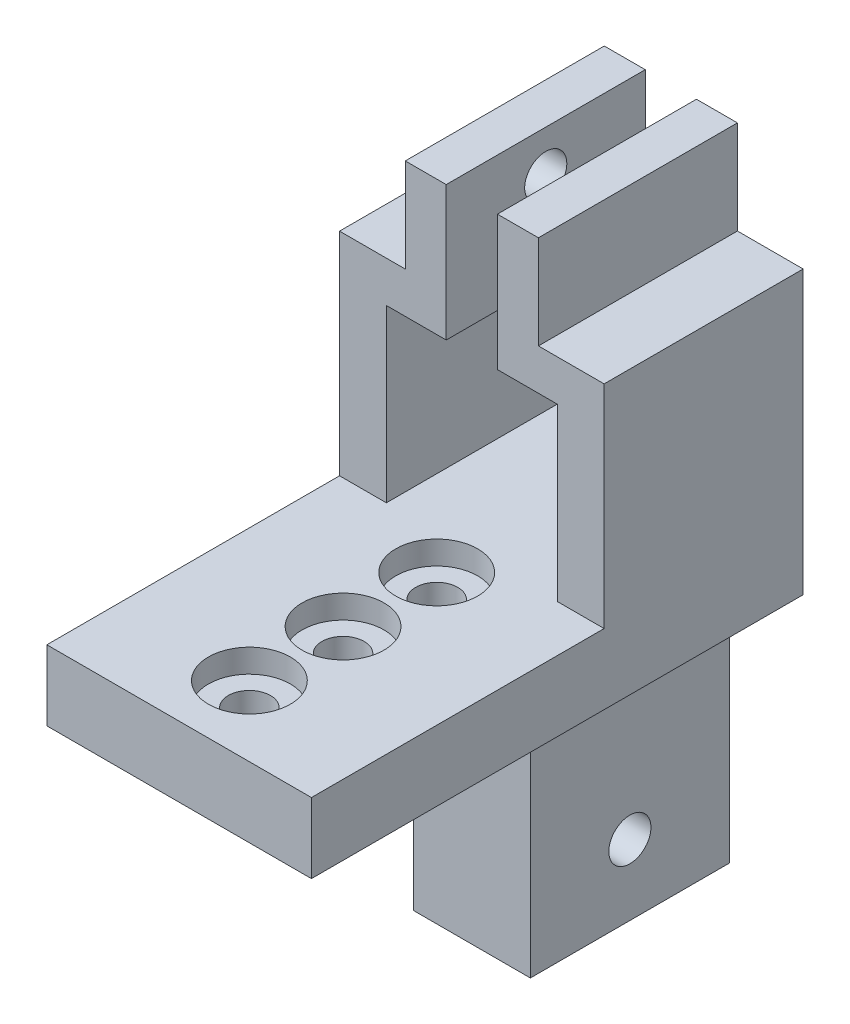
SolidWorks part; units mm, degrees
ref_plane "Front Plane" through (0, 0, 0) normal (0, 0, 1) x (1, 0, 0)
ref_plane "Top Plane" through (0, 0, 0) normal (0, 1, 0) x (1, 0, 0)
ref_plane "Right Plane" through (0, 0, 0) normal (1, 0, 0) x (0, 0, -1)
sketch "Sketch2" plane through (0, 0, 0) normal (0, 0, 1) x (1, 0, 0)
  line L0 (-7.5263, 9.46) -> (-7.5263, -5.14)
  line L1 (-7.5263, -5.14) -> (7.0737, -5.14)
  line L2 (7.0737, -5.14) -> (7.0737, 9.46)
  line L3 (7.0737, 9.46) -> (1.9603, 9.46)
  line L4 (-7.5263, 9.46) -> (-2.4129, 9.46)
  line L5 (-5.9129, 12.96) -> (-5.9129, 20.96)
  line L6 (-5.9129, 12.96) -> (-11.5263, 12.96)
  line L7 (-11.5263, 12.96) -> (-11.5263, -11.14)
  line L8 (-11.5263, -11.14) -> (11.0737, -11.14)
  line L9 (11.0737, -11.14) -> (11.0737, 12.96)
  line L10 (11.0737, 12.96) -> (5.4603, 12.96)
  line L11 (-5.9129, 20.96) -> (-2.4129, 20.96)
  line L12 (-2.4129, 20.96) -> (-2.4129, 9.46)
  line L13 (1.9603, 9.46) -> (1.9603, 20.96)
  line L14 (1.9603, 20.96) -> (5.4603, 20.96)
  line L15 (5.4603, 20.96) -> (5.4603, 12.96)
  dimension "D1" = 14.6
  dimension "D2" = 4
  dimension "D3" = 6
  dimension "D4" = 4
  dimension "D5" = 3.5
  dimension "D6" = 3.5
  dimension "D7" = 14.6
  dimension "D8" = 8
extrude "Boss-Extrude1" add sketch "Sketch2" along normal blind 17
sketch "Sketch3" plane through (0, 0, 17) normal (0, 0, 1) x (1, 0, 0)
  line L0 (-11.5263, -11.14) -> (11.0737, -11.14) construction
  line L1 (-5.2263, -11.14) -> (4.7737, -11.14)
  line L2 (-5.2263, -11.14) -> (-5.2263, -34.14)
  line L3 (-5.2263, -34.14) -> (4.7737, -34.14)
  line L4 (4.7737, -11.14) -> (4.7737, -34.14)
  line L5 (-0.2263, -11.14) -> (-0.2263, 19.7191) construction
  dimension "D1" = 10
  dimension "D2" = 23
extrude "Boss-Extrude2" add sketch "Sketch3" against normal up to surface (17 mm away) up to face at (-0.2263, 8.81, 0)
sketch "Sketch4" plane through (4.7737, 0, 0) normal (1, 0, 0) x (0, 0, -1)
  line L0 (-8.5, -34.14) -> (-8.5, 20.96) construction
  line L1 (0, -34.14) -> (-17, -34.14) construction
  line L2 (-17, 20.96) -> (0, 20.96) construction
  circle A0 centre (-8.5, -28.14) radius 1.8
  circle A1 centre (-8.5, 17.36) radius 1.8
  dimension "D1" = 3.6
  dimension "D2" = 3.6
  dimension "D3" = 6
extrude "Cut-Extrude1" cut sketch "Sketch4" against normal through all
sketch "Sketch5" plane through (0, 0, 17) normal (0, 0, 1) x (1, 0, 0)
  line L0 (7.0737, -5.14) -> (-7.5263, -5.14) construction
  line L1 (-11.5263, -11.14) -> (11.0737, -11.14)
  line L2 (-11.5263, -11.14) -> (-11.5263, -5.14)
  line L3 (-11.5263, -5.14) -> (11.0737, -5.14)
  line L4 (11.0737, -11.14) -> (11.0737, -5.14)
  line L5 (11.0737, -11.14) -> (11.0737, 12.96) construction
extrude "Boss-Extrude3" add sketch "Sketch5" along normal blind 25
sketch "Sketch6" plane through (0, -5.14, 0) normal (0, 1, 0) x (1, 0, 0)
  line L0 (-0.2263, -42) -> (-0.2263, 5.0846) construction
  line L1 (11.0737, -42) -> (-11.5263, -42) construction
  circle A0 centre (-0.2263, -36) radius 1.8
  circle A1 centre (-0.2263, -28) radius 1.8
  circle A2 centre (-0.2263, -20) radius 1.8
  dimension "D1" = 3.6
  dimension "D2" = 6
  dimension "D3" = 14
  dimension "D4" = 22
extrude "Cut-Extrude2" cut sketch "Sketch6" against normal through all
sketch "Sketch7" plane through (0, -5.14, 0) normal (0, 1, 0) x (1, 0, 0)
  circle A0 centre (-0.2263, -36) radius 3.5
  circle A1 centre (-0.2263, -28) radius 3.5
  circle A2 centre (-0.2263, -20) radius 3.5
  circle A3 centre (-0.2263, -36) radius 1.8 construction
  circle A4 centre (-0.2263, -28) radius 1.8 construction
  circle A5 centre (-0.2263, -20) radius 1.8 construction
  dimension "D1" = 7
extrude "Cut-Extrude3" cut sketch "Sketch7" against normal blind 2
